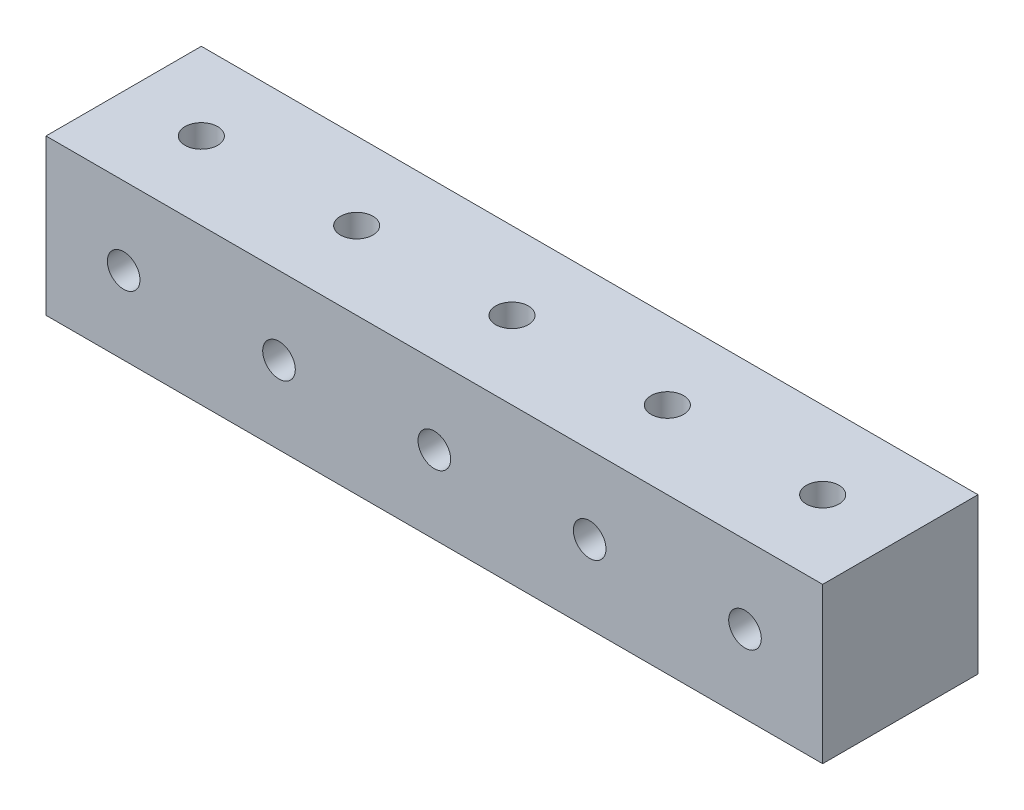
SolidWorks part; units mm, degrees
ref_plane "前视基准面" through (0, 0, 0) normal (0, 0, 1) x (1, 0, 0)
ref_plane "上视基准面" through (0, 0, 0) normal (0, 1, 0) x (1, 0, 0)
ref_plane "右视基准面" through (0, 0, 0) normal (1, 0, 0) x (0, 0, -1)
sketch "草图1" plane through (0, 0, 0) normal (1, 0, 0) x (0, 0, -1)
  line L1 (-10, 10) -> (10, 10)
  line L2 (-10, 10) -> (-10, -10)
  line L3 (-10, -10) -> (10, -10)
  line L4 (10, 10) -> (10, -10)
  line L5 (-10, 10) -> (10, -10) construction
  line L6 (-10, -10) -> (10, 10) construction
  point P0 (0, 0)
  dimension "D1" = 20
  dimension "D2" = 20
extrude "凸台-拉伸1" add sketch "草图1" along normal blind 100
sketch "草图2" plane through (0, 0, 10) normal (0, 0, 1) x (1, 0, 0)
  line L0 (100, 10) -> (0, 10) construction
  circle A0 centre (10, 0) radius 2.1
  circle A1 centre (30, 0) radius 2.1
  circle A2 centre (50, 0) radius 2.1
  circle A3 centre (70, 0) radius 2.1
  circle A4 centre (90, 0) radius 2.1
  dimension "D1" = 4.2
  dimension "D2" = 10
  dimension "D3" = 10
  dimension "D5" = 20
  dimension "D4" = 5
extrude "切除-拉伸1" cut sketch "草图2" against normal blind 100
sketch "草图3" plane through (0, 10, 0) normal (0, 1, 0) x (1, 0, 0)
  line L0 (0, 10) -> (0, -10) construction
  line L1 (100, 10) -> (0, 10) construction
  circle A0 centre (10, 0) radius 2.1
  circle A1 centre (30, 0) radius 2.1
  circle A2 centre (50, 0) radius 2.1
  circle A3 centre (70, 0) radius 2.1
  circle A4 centre (90, 0) radius 2.1
  dimension "D1" = 10
  dimension "D3" = 4.2
  dimension "D2" = 10
  dimension "D5" = 20
  dimension "D4" = 5
extrude "切除-拉伸2" cut sketch "草图3" against normal through all
